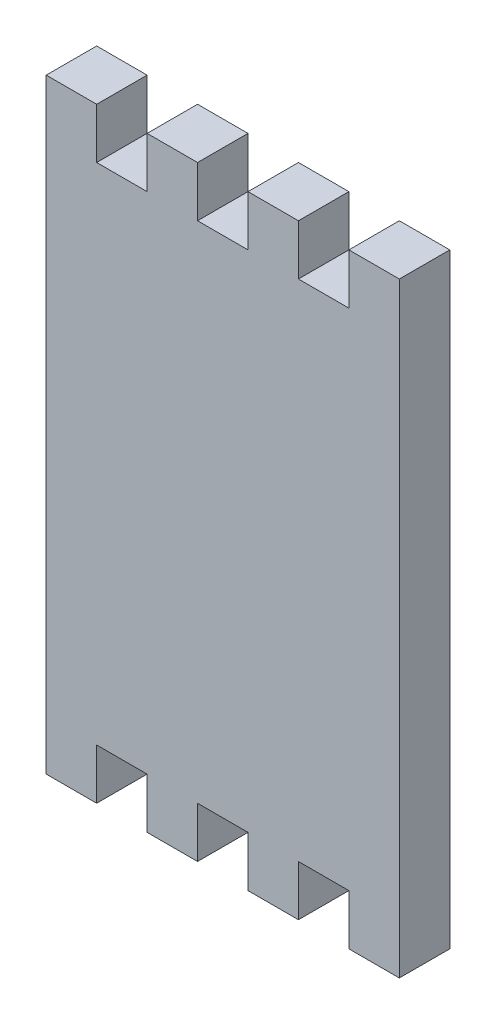
SolidWorks part; units mm, degrees
ref_plane "Front Plane" through (0, 0, 0) normal (0, 0, 1) x (1, 0, 0)
ref_plane "Top Plane" through (0, 0, 0) normal (0, 1, 0) x (1, 0, 0)
ref_plane "Right Plane" through (0, 0, 0) normal (1, 0, 0) x (0, 0, -1)
sketch "Sketch1" plane through (0, 0, 0) normal (0, 0, 1) x (1, 0, 0)
  line L0 (23.1164, 13.1799) -> (23.1164, -3.8201) construction
  line L5 (12.6164, 16.1799) -> (15.6164, 16.1799)
  line L38 (12.6164, 16.1799) -> (12.6164, -19.8201)
  line L39 (12.6164, -19.8201) -> (15.6164, -19.8201)
  line L40 (33.6164, 16.1799) -> (33.6164, -19.8201)
  line L42 (15.6164, -16.8201) -> (15.6164, -19.8201)
  line L43 (12.6164, -1.8201) -> (33.6164, -1.8201) construction
  line L45 (30.6164, -16.8201) -> (30.6164, -19.8201)
  line L46 (30.6164, 13.1799) -> (30.6164, 16.1799)
  line L47 (30.6164, 13.1799) -> (27.6164, 13.1799)
  line L48 (27.6164, 13.1799) -> (27.6164, 16.1799)
  line L49 (24.6164, 13.1799) -> (24.6164, 16.1799)
  line L50 (21.6164, 13.1799) -> (24.6164, 13.1799)
  line L51 (21.6164, 13.1799) -> (21.6164, 16.1799)
  line L52 (18.6164, 13.1799) -> (18.6164, 16.1799)
  line L53 (15.6164, 13.1799) -> (18.6164, 13.1799)
  line L54 (15.6164, 13.1799) -> (15.6164, 16.1799)
  line L55 (24.6164, 16.1799) -> (27.6164, 16.1799)
  line L56 (18.6164, 16.1799) -> (21.6164, 16.1799)
  line L57 (30.6164, 16.1799) -> (33.6164, 16.1799)
  line L58 (30.6164, -19.8201) -> (33.6164, -19.8201)
  line L62 (15.6164, -16.8201) -> (18.6164, -16.8201)
  line L63 (27.6164, -16.8201) -> (27.6164, -19.8201)
  line L64 (24.6164, -19.8201) -> (27.6164, -19.8201)
  line L65 (24.6164, -16.8201) -> (24.6164, -19.8201)
  line L66 (21.6164, -16.8201) -> (21.6164, -19.8201)
  line L67 (18.6164, -19.8201) -> (21.6164, -19.8201)
  line L68 (18.6164, -16.8201) -> (18.6164, -19.8201)
  line L69 (21.6164, -16.8201) -> (24.6164, -16.8201)
  line L70 (27.6164, -16.8201) -> (30.6164, -16.8201)
  dimension "D1" = 21
  dimension "D2" = 36
  dimension "D3" = 3
extrude "Boss-Extrude1" add sketch "Sketch1" along normal blind 3
